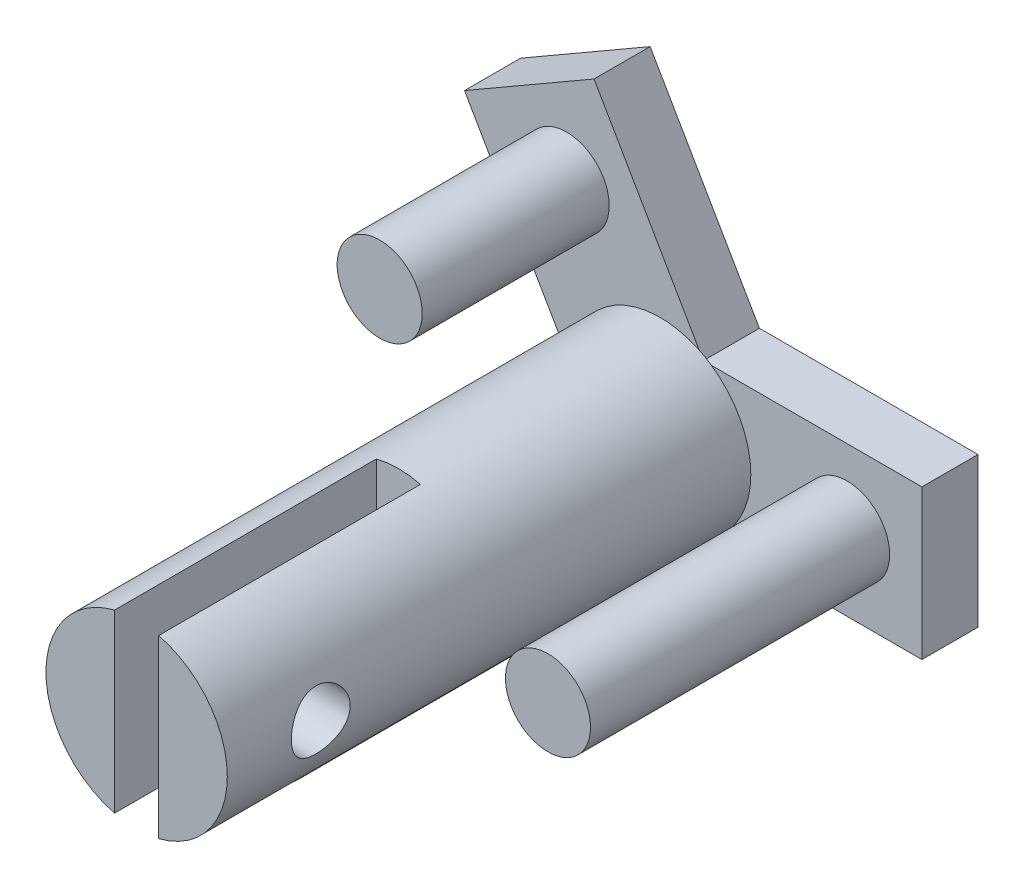
SolidWorks part; units mm, degrees
ref_plane "Front Plane" through (0, 0, 0) normal (0, 0, 1) x (1, 0, 0)
ref_plane "Top Plane" through (0, 0, 0) normal (0, 1, 0) x (1, 0, 0)
ref_plane "Right Plane" through (0, 0, 0) normal (1, 0, 0) x (0, 0, -1)
sketch "Sketch1" plane through (0, 0, 0) normal (0, 0, 1) x (1, 0, 0)
  circle A0 centre (0, 0) radius 4.85
extrude "Boss-Extrude1" add sketch "Sketch1" along normal blind 28
sketch "Sketch2" plane through (0, 0, 28) normal (0, 0, 1) x (1, 0, 0)
  line L1 (-1.18, -5) -> (1.18, -5)
  line L2 (-1.18, -5) -> (-1.18, 5)
  line L3 (-1.18, 5) -> (1.18, 5)
  line L4 (1.18, -5) -> (1.18, 5)
  line L5 (-1.18, -5) -> (1.18, 5) construction
  line L6 (-1.18, 5) -> (1.18, -5) construction
  point P0 (0, 0)
  dimension "D1" = 2.36
  dimension "D2" = 10
extrude "Cut-Extrude1" cut sketch "Sketch2" against normal blind 14
sketch "Sketch3" plane through (1.18, 0, 0) normal (-1, 0, 0) x (0, 0, 1)
  line L0 (28, 0) -> (17.745, 0) construction
  line L1 (28, -4.7043) -> (28, 4.7043) construction
  circle A0 centre (23, 0) radius 1.575
  dimension "D1" = 5
  dimension "D2" = 3.15
extrude "Cut-Extrude2" cut sketch "Sketch3" against normal through all and the other way through all
sketch "Sketch5" plane through (0, 0, 0) normal (0, 0, -1) x (-1, 0, 0)
  line L0 (0, 0) -> (-4.85, 0) construction
  line L1 (0, 0) -> (2.425, -4.2002) construction
  line L2 (0, 0) -> (2.425, 4.2002) construction
  line L3 (0, 0) -> (-2.3094, -4) construction
  line L4 (0, 0) -> (-2.3094, 4) construction
  line L5 (0, 0) -> (4.6188, 0) construction
  line L6 (-2.3094, -4) -> (-14, -4)
  line L7 (-14, -4) -> (-14, 4)
  line L8 (-14, 4) -> (-2.3094, 4)
  line L9 (-2.3094, 4) -> (3.5359, 14.1244)
  line L10 (3.5359, 14.1244) -> (10.4641, 10.1244)
  line L11 (10.4641, 10.1244) -> (4.6188, 0)
  line L12 (4.6188, 0) -> (10.4641, -10.1244)
  line L13 (10.4641, -10.1244) -> (3.5359, -14.1244)
  line L14 (3.5359, -14.1244) -> (-2.3094, -4)
  circle A0 centre (0, 0) radius 4.85 construction
  dimension "D1" = 120
  dimension "D2" = 120
  dimension "D3" = 120
  dimension "D4" = 120
  dimension "D5" = 120
  dimension "D6" = 90
  dimension "D7" = 90
  dimension "D8" = 90
  dimension "D9" = 60
  dimension "D10" = 60
  dimension "D11" = 14
  dimension "D12" = 14
  dimension "D13" = 14
  dimension "D14" = 8
  dimension "D15" = 8
  dimension "D16" = 8
extrude "Boss-Extrude2" add sketch "Sketch5" along normal blind 3
sketch "Sketch6" plane through (0, 0, 0) normal (0, 0, 1) x (1, 0, 0)
  line L0 (-7, -12.1244) -> (0, 0) construction
  line L1 (-3.5359, -14.1244) -> (-10.4641, -10.1244) construction
  line L2 (0, 0) -> (-7, 12.1244) construction
  line L3 (-10.4641, 10.1244) -> (-3.5359, 14.1244) construction
  line L4 (-7, 12.1244) -> (14, 0) construction
  line L5 (14, 4) -> (14, -4) construction
  line L6 (14, 0) -> (0, 0) construction
  circle A0 centre (-5, 8.6603) radius 2.275
  circle A1 centre (-5, -8.6603) radius 2.275
  circle A2 centre (10, 0) radius 2.275
  dimension "D1" = 10
  dimension "D2" = 10
  dimension "D3" = 10
  dimension "D4" = 4.55
  dimension "D5" = 4.55
  dimension "D6" = 4.55
extrude "Boss-Extrude3" add sketch "Sketch6" along normal blind 16
sketch "Sketch7" plane through (0, 0, 16) normal (0, 0, 1) x (1, 0, 0)
  circle A1 centre (-5, 8.6603) radius 2.275
  circle A2 centre (-5, 8.6603) radius 2.275
  dimension "D1" = 0
extrude "Cut-Extrude3" cut sketch "Sketch7" against normal blind 6
